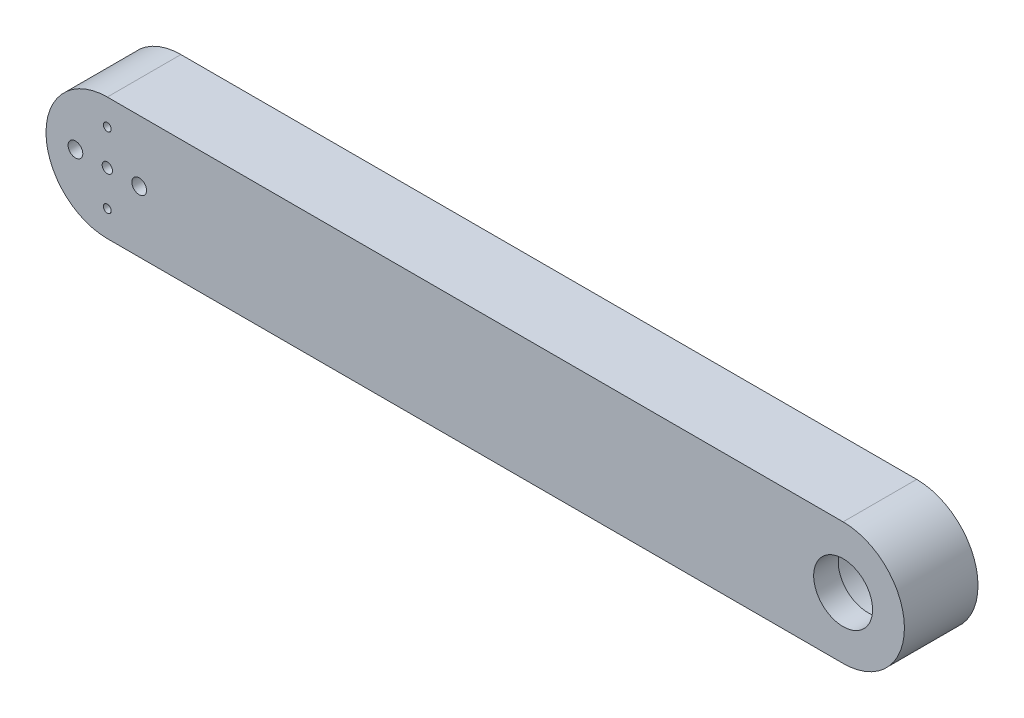
SolidWorks part; units mm, degrees
ref_plane "正面" through (0, 0, 0) normal (0, 0, 1) x (1, 0, 0)
ref_plane "平面" through (0, 0, 0) normal (0, 1, 0) x (1, 0, 0)
ref_plane "右側面" through (0, 0, 0) normal (1, 0, 0) x (0, 0, -1)
sketch "ｽｹｯﾁ2" plane through (0, 0, 0) normal (0, 0, 1) x (1, 0, 0)
  line L1 (-75, 12.5) -> (75, 12.5)
  line L2 (-75, 12.5) -> (-75, -12.5)
  line L3 (-75, -12.5) -> (75, -12.5)
  line L4 (75, 12.5) -> (75, -12.5)
  line L5 (-75, 12.5) -> (75, -12.5) construction
  line L6 (-75, -12.5) -> (75, 12.5) construction
  circle A0 centre (-75, 0) radius 12.5
  circle A1 centre (75, 0) radius 12.5
  circle A2 centre (-75, 0) radius 1.05
  circle A3 centre (75, 0) radius 1.05
  point P0 (0, 0)
  dimension "D3" = 2.1
  dimension "D4" = 2.1
  dimension "D1" = 25
  dimension "D2" = 150
extrude "ﾎﾞｽ - 押し出し1" add sketch "ｽｹｯﾁ2" along normal blind 15 contours A2 L2 A0 | A2 L2 A0 | A1 L1 A0 L3 | A3 L4 A1 | A3 L4 A1
sketch "ｽｹｯﾁ7" plane through (0, 0, 0) normal (0, 0, 1) x (1, 0, 0)
  circle A0 centre (-75, 0) radius 6.5
  circle A1 centre (-68.5, 0) radius 1.5
  circle A2 centre (-81.5, 0) radius 1.5
  dimension "D1" = 13
  dimension "D2" = 3
  dimension "D3" = 3
extrude "ｶｯﾄ - 押し出し3" cut sketch "ｽｹｯﾁ7" against normal through all and the other way through all contours A0 A1 | A0 A1 | A0 A2 | A0 A2
sketch "ｽｹｯﾁ8" plane through (0, 0, 0) normal (0, 0, 1) x (1, 0, 0)
  circle A0 centre (75, 0) radius 9.5
  dimension "D1" = 19
extrude "ｶｯﾄ - 押し出し4" cut sketch "ｽｹｯﾁ8" along normal blind 10 contours A0
sketch "ｽｹｯﾁ9" plane through (0, 0, 0) normal (0, 0, 1) x (1, 0, 0)
  circle A0 centre (75, 0) radius 6
  dimension "D1" = 12
extrude "ｶｯﾄ - 押し出し10" cut sketch "ｽｹｯﾁ9" along normal blind 20
hole_wizard "M2x0.4 ねじ穴1" positions "ｽｹｯﾁ3" profile "ｽｹｯﾁ4" tap size "M2x0.4" standard "JIS" end condition through all
sketch "ｽｹｯﾁ3" plane through (0, 0, 15) normal (0, 0, 1) x (1, 0, 0)
  circle A0 centre (-75, 0) radius 1.05
  point P0 (-75, 7.2)
  point P2 (-67.8, 0)
  point P4 (-67.8, 0)
  point P6 (-75, -7.2)
  dimension "D1" = 7.2
  dimension "D2" = 0
  dimension "D3" = 7.2
  dimension "D4" = 0
  dimension "D5" = 7.2
  dimension "D6" = 7.2
sketch "ｽｹｯﾁ4" plane through (-75, 7.2, 15) normal (1, 0, 0) x (0, -1, 0)
  line L0 (0, 0) -> (0, 15)
  line L1 (0, 15) -> (0.8, 15)
  line L2 (0.8, 15) -> (0.8, 0)
  line L5 (0.8, 0) -> (0, 0)
  line L11 (0, -6.35) -> (0, 107.95) construction
  dimension "次ｻｰﾌｪｽまでのねじ下穴ﾄﾞﾘﾙ直径" = 1.6
  dimension "次ｻｰﾌｪｽまでのねじ下穴ﾄﾞﾘﾙの深さ" = 15
cosmetic thread "穴のねじ山1" parameters "D2"=2
cosmetic thread "穴のねじ山4" parameters "D2"=2
hole_wizard "M2x0.4 ねじ穴2" positions "ｽｹｯﾁ5" profile "ｽｹｯﾁ6" tap size "M2x0.4" standard "JIS" end condition through all
sketch "ｽｹｯﾁ5" plane through (0, 0, 15) normal (0, 0, 1) x (1, 0, 0)
  circle A0 centre (-75, 0) radius 1.05
  point P0 (-67.8, 0)
  dimension "D1" = 7.2
sketch "ｽｹｯﾁ6" plane through (-67.8, 0, 15) normal (1, 0, 0) x (0, -1, 0)
  line L0 (0, 0) -> (0, 15)
  line L1 (0, 15) -> (0.8, 15)
  line L2 (0.8, 15) -> (0.8, 0)
  line L5 (0.8, 0) -> (0, 0)
  line L11 (0, -6.35) -> (0, 107.95) construction
  dimension "次ｻｰﾌｪｽまでのねじ下穴ﾄﾞﾘﾙ直径" = 1.6
  dimension "次ｻｰﾌｪｽまでのねじ下穴ﾄﾞﾘﾙの深さ" = 15
